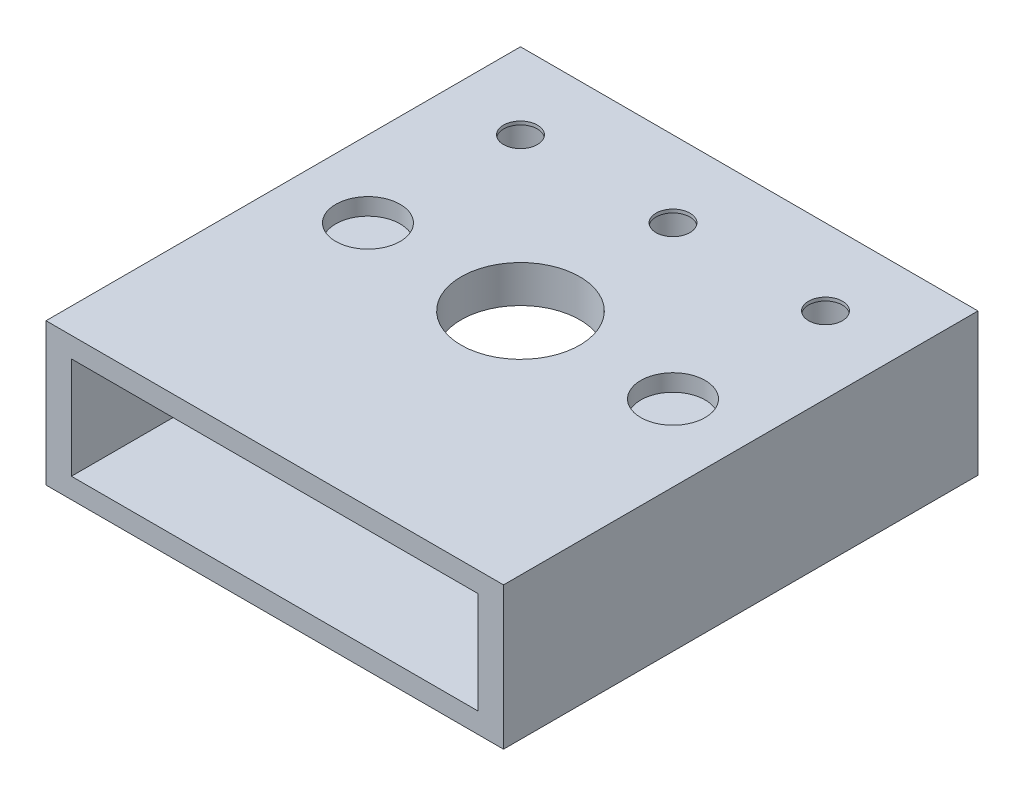
SolidWorks part; units mm, degrees
ref_plane "Front Plane" through (0, 0, 0) normal (0, 0, 1) x (1, 0, 0)
ref_plane "Top Plane" through (0, 0, 0) normal (0, 1, 0) x (1, 0, 0)
ref_plane "Right Plane" through (0, 0, 0) normal (1, 0, 0) x (0, 0, -1)
sketch "Sketch1" plane through (0, 0, 0) normal (0, 1, 0) x (1, 0, 0)
  line L1 (-67.5, -45) -> (67.5, -45)
  line L2 (-67.5, -45) -> (-67.5, 45)
  line L3 (-67.5, 45) -> (67.5, 45)
  line L4 (67.5, -45) -> (67.5, 45)
  line L5 (-67.5, -45) -> (67.5, 45) construction
  line L6 (-67.5, 45) -> (67.5, -45) construction
  line L8 (-67.5, 0) -> (-67.5, -22.5)
  circle A0 centre (0, -22.5) radius 17.5
  point P0 (0, 0)
  point P9 (0, 0)
  point P12 (0, 0)
extrude "Boss-Extrude1" add sketch "Sketch1" along normal blind 11 contours L1 L4 L3 L2 A0
sketch "Sketch3" plane through (0, 11, 0) normal (0, 1, 0) x (1, 0, 0)
  circle A0 centre (-45, -22.5) radius 9.5
  circle A1 centre (45, -22.5) radius 9.5
  point P4 (0, 0)
  point P8 (0, 0)
  point P13 (0, -22.5)
extrude "Cut-Extrude1" cut sketch "Sketch3" against normal blind 5 contours A1 | A0
sketch "Sketch5" plane through (0, 11, 0) normal (0, 1, 0) x (1, 0, 0)
  circle A0 centre (0, 22.5) radius 5
  circle A1 centre (-45, 22.5) radius 5
  circle A2 centre (45, 22.5) radius 5
extrude "Cut-Extrude2" cut sketch "Sketch5" against normal through all both and the other way through all contours A0 | A2 | A1
sketch "Sketch6" plane through (0, 0, 0) normal (0, -1, 0) x (1, 0, 0)
  circle A0 centre (45, -22.5) radius 8
  circle A1 centre (0, -22.5) radius 8
  circle A2 centre (-45, -22.5) radius 8
  point P4 (0, 0)
  point P8 (0, 0)
extrude "Cut-Extrude3" cut sketch "Sketch6" against normal blind 10
sketch "Sketch7" plane through (0, 0, 0) normal (0, -1, 0) x (1, 0, 0)
  line L1 (-67.5, 45) -> (67.5, 45)
  line L2 (-67.5, 45) -> (-67.5, -45)
  line L3 (-67.5, -45) -> (67.5, -45)
  line L4 (67.5, 45) -> (67.5, -45)
  line L5 (-55, -41) -> (55, -41)
  line L6 (-55, -41) -> (-55, 41)
  line L7 (-55, 41) -> (55, 41)
  line L8 (55, -41) -> (55, 41)
  line L9 (-55, -41) -> (55, 41) construction
  line L10 (-55, 41) -> (55, -41) construction
  point P4 (0, 0)
extrude "Boss-Extrude2" add sketch "Sketch7" along normal blind 31
sketch "Sketch8" plane through (0, 0, 45) normal (0, 0, 1) x (1, 0, 0)
  line L1 (-67.5, 11) -> (67.5, 11)
  line L2 (-67.5, 11) -> (-67.5, -31)
  line L3 (-67.5, -31) -> (67.5, -31)
  line L4 (67.5, 11) -> (67.5, -31)
extrude "Boss-Extrude3" add sketch "Sketch8" along normal blind 50
sketch "Sketch9" plane through (0, 0, 95) normal (0, 0, 1) x (1, 0, 0)
  line L0 (0, 28.6194) -> (0, -51.8045) construction
  line L1 (-67.5, -10) -> (67.5, -10) construction
  line L2 (-67.5, 11) -> (-67.5, -31) construction
  line L3 (67.5, -31) -> (67.5, 11) construction
  line L5 (60, -25) -> (-60, -25)
  line L6 (60, -25) -> (60, 5)
  line L7 (60, 5) -> (-60, 5)
  line L8 (-60, -25) -> (-60, 5)
  line L9 (60, -25) -> (-60, 5) construction
  line L10 (60, 5) -> (-60, -25) construction
  point P9 (0, -10)
  point P10 (0, -10)
extrude "Cut-Extrude4" cut sketch "Sketch9" against normal blind 35
sketch "Sketch10" plane through (0, 0, 60) normal (0, 0, 1) x (1, 0, 0)
  line L0 (-60, -10) -> (60, -10) construction
  line L5 (0, 5) -> (0, -25) construction
  circle A0 centre (-40, -10) radius 5
  circle A1 centre (40, -10) radius 5
  circle A2 centre (0, -10) radius 5
extrude "Cut-Extrude5" cut sketch "Sketch10" against normal up to surface (101 mm away) up to face at (0, -15.5, -41)
sketch "Sketch11" plane through (0, 0, 41) normal (0, 0, -1) x (-1, 0, 0)
  circle A0 centre (0, -10) radius 8
  circle A1 centre (-40, -10) radius 8
  circle A2 centre (40, -10) radius 8
extrude "Cut-Extrude6" cut sketch "Sketch11" against normal blind 10
